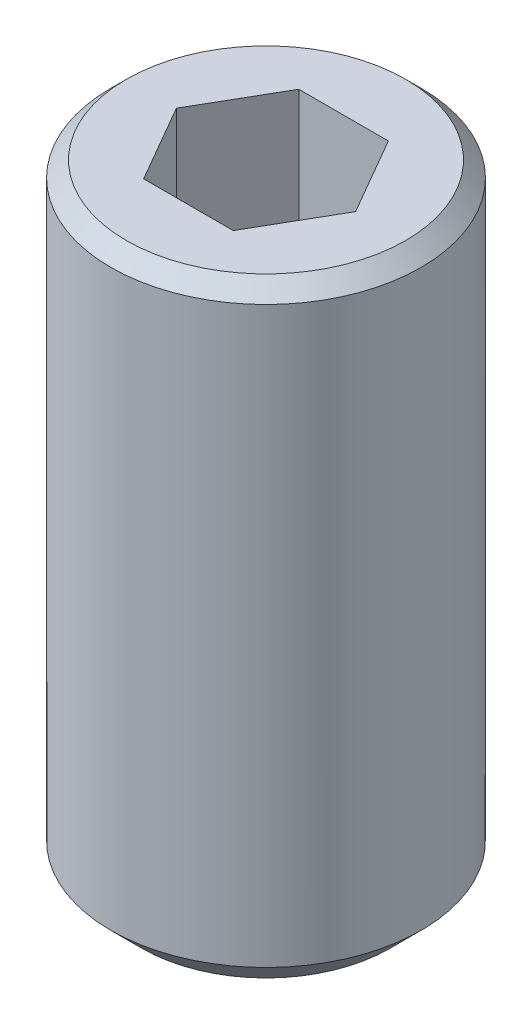
SolidWorks part; units mm, degrees
material "acero"
ref_plane "Alzado" through (0, 0, 0) normal (0, 0, 1) x (1, 0, 0)
ref_plane "Planta" through (0, 0, 0) normal (0, 1, 0) x (1, 0, 0)
ref_plane "Vista lateral" through (0, 0, 0) normal (1, 0, 0) x (0, 0, -1)
sketch "Croquis1" plane through (0, 0, 0) normal (0, 0, 1) x (1, 0, 0)
  line L0 (0, 0) -> (0, -60.9498) construction
  line L1 (0, 0) -> (1.5, 0)
  line L4 (1.5, 0) -> (1.5, -6)
  line L5 (1.5, -6) -> (0, -6)
  line L6 (0, -6) -> (0, 0)
  dimension "D1" = 6
  dimension "D4" = 3
revolve "Revolución1" add sketch "Croquis1" angle 360 about L0
sketch "Croquis3" plane through (0, 0, 0) normal (0, 1, 0) x (1, 0, 0)
  line L1 (-0.433, 0.75) -> (-0.866, 0)
  line L2 (-0.866, 0) -> (-0.433, -0.75)
  line L3 (-0.433, -0.75) -> (0.433, -0.75)
  line L4 (0.433, -0.75) -> (0.866, 0)
  line L5 (0.866, 0) -> (0.433, 0.75)
  line L6 (0.433, 0.75) -> (-0.433, 0.75)
  circle A0 centre (0, 0) radius 0.75 construction
  dimension "D1" = 1.5
extrude "Cortar-Extruir2" cut sketch "Croquis3" against normal blind 1.5
chamfer "Chaflán3" distance 0.3 angle 45 1 edges at (0, -6, 1.5)
chamfer "Chaflán4" distance 0.15 angle 45 1 edges at (0, 0, 1.5)
